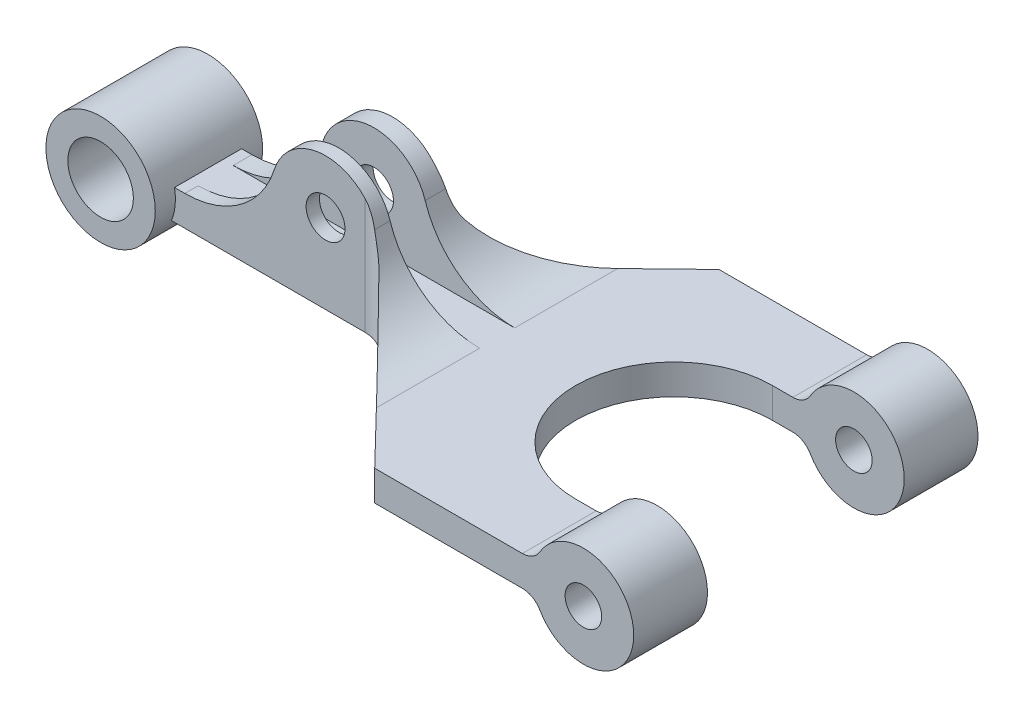
SolidWorks part; units mm, degrees
material "Cast Carbon Steel"
ref_plane "Front Plane" through (0, 0, 0) normal (0, 0, 1) x (1, 0, 0)
ref_plane "Top Plane" through (0, 0, 0) normal (0, 1, 0) x (1, 0, 0)
ref_plane "Right Plane" through (0, 0, 0) normal (1, 0, 0) x (0, 0, -1)
sketch "Sketch1" plane through (0, 0, 0) normal (0, 0, 1) x (1, 0, 0)
  circle A0 centre (12.7411, -63.1344) radius 2.9
  circle A1 centre (12.7411, -63.1344) radius 8
extrude "Extrude1" add sketch "Sketch1" against normal blind 10
ref_plane "Plane4" through (0, -71, 0) normal (0, 1, 0) x (-1, 0, 0)
sketch "Sketch2" plane through (0, -71, 0) normal (0, 1, 0) x (-1, 0, 0)
  line L0 (-12.7411, 0) -> (12.9084, 0)
  line L1 (-9.8411, 0) -> (-15.6411, 0) construction
  line L2 (12.9084, 0) -> (12.9084, -10)
  line L3 (12.9084, -10) -> (-12.7411, -10)
  line L4 (-20.7411, -10) -> (-4.7411, -10) construction
  line L5 (-12.7411, -10) -> (-20.7411, -10)
  line L6 (-20.7411, -10) -> (-41.3922, -30)
  line L7 (-60.3431, 10.3234) -> (-65.3431, 10.3234)
  line L8 (-65.3431, -19) -> (-60.3431, -19)
  line L9 (-41.3922, 21.3234) -> (-65.3431, 21.3234)
  line L10 (-41.3922, -30) -> (-65.3431, -30)
  line L11 (-65.3431, -30) -> (-65.3431, -19)
  line L12 (-65.3431, 21.3234) -> (-65.3431, 10.3234)
  line L13 (-20.7411, 0) -> (-41.3922, 21.3234)
  line L14 (-60.3431, 10.3234) -> (-60.3431, -19) construction
  line L16 (-20.7411, 0) -> (-12.7411, 0)
  arc A0 (-60.3431, -19) -> (-60.3431, 10.3234) centre (-60.3431, -4.3383) ccw
  dimension "D1" = 11
  dimension "D5" = 20
  dimension "D6" = 11
extrude "Extrude2" add sketch "Sketch2" along normal blind 0.5 and the other way blind 4
sketch "Sketch4" plane through (0, 0, 0) normal (1, 0, 0) x (0, 0, -1)
  line L1 (1.9919, -52.3482) -> (7.2199, -52.3482)
  line L2 (1.9919, -52.3482) -> (1.9919, -70.5)
  line L3 (1.9919, -70.5) -> (7.2199, -70.5)
  line L4 (7.2199, -52.3482) -> (7.2199, -70.5)
extrude "Cut-Extrude1" cut sketch "Sketch4" along normal through all
fillet "Fillet4" radius 14 4 edges at (9.6191, -70.5, -0.9959) (15.8632, -70.5, -0.9959) (15.8632, -70.5, -8.6099) (9.6191, -70.5, -8.6099)
sketch "Sketch6" plane through (0, 0, 21.3234) normal (0, 0, 1) x (1, 0, 0)
  circle A0 centre (72.4977, -72.75) radius 2.7266
  circle A1 centre (72.4977, -72.75) radius 7.5
extrude "Extrude4" add sketch "Sketch6" against normal blind 11
ref_plane "Plane5" [suppressed] through (0, 0, -10) normal (0, 0, 1) x (1, 0, 0)
sketch "Sketch8" plane through (0, 0, -30) normal (0, 0, 1) x (1, 0, 0)
  circle A0 centre (72.4977, -72.75) radius 7.5
  circle A1 centre (72.4977, -72.75) radius 2.725
sketch "Sketch11" plane through (0, 0, 0) normal (0, 0, 1) x (1, 0, 0)
  circle A0 centre (-17.7936, -71.9602) radius 8.1518
  circle A1 centre (-17.7936, -71.9602) radius 4.8851
extrude "Extrude6" add sketch "Sketch11" against normal blind 13 and the other way blind 3
extrude "Extrude7" add sketch "Sketch8" along normal blind 11
fillet "Fillet19" radius 3 4 edges at (65.3431, -75, 15.8234) (65.3431, -70.5, 15.8234) (65.3431, -75, -24.5) (65.3431, -70.5, -24.5)
fillet "Fillet23" radius 5 2 edges at (20.7411, -68.3781, -10) (20.7411, -68.3781, 0)
ref_plane "MidPlane - arm" through (0, 0, -4.6049) normal (0, 0, 1) x (1, 0, 0)
